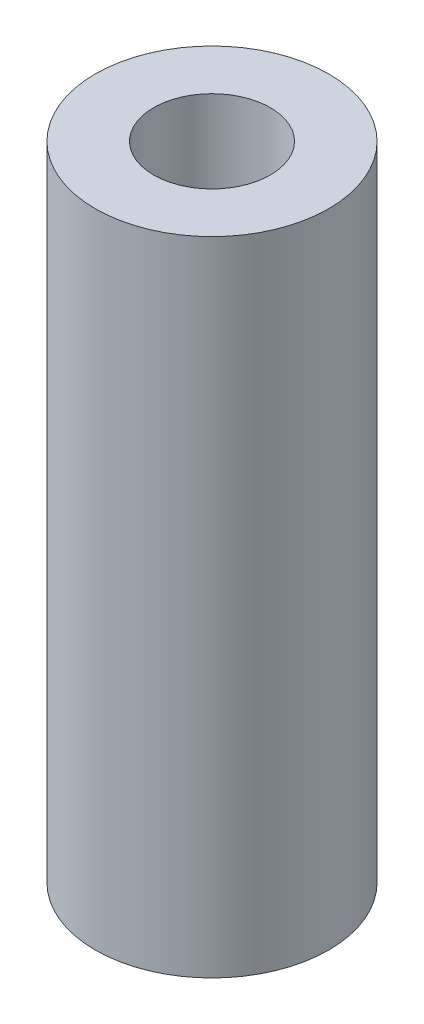
SolidWorks part; units mm, degrees
material "6061-T6 (SS)"
ref_plane "Front Plane" through (0, 0, 0) normal (0, 0, 1) x (1, 0, 0)
ref_plane "Top Plane" through (0, 0, 0) normal (0, 1, 0) x (1, 0, 0)
ref_plane "Right Plane" through (0, 0, 0) normal (1, 0, 0) x (0, 0, -1)
sketch "Sketch1" plane through (0, 0, 0) normal (0, 1, 0) x (1, 0, 0)
  circle A0 centre (0, 0) radius 3.175
  circle A1 centre (0, 0) radius 6.35
  dimension "D1" = 12.7
  dimension "D2" = 6.35
extrude "Boss-Extrude1" add sketch "Sketch1" along normal blind 34.925
